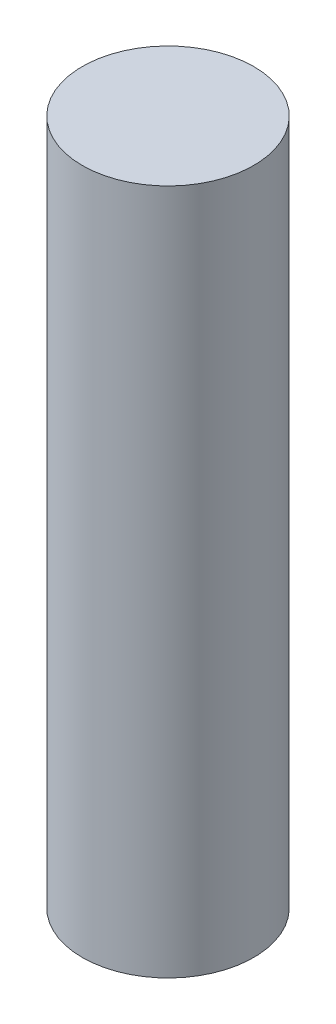
SolidWorks part; units mm, degrees
ref_plane "Alzado" through (0, 0, 0) normal (0, 0, 1) x (1, 0, 0)
ref_plane "Planta" through (0, 0, 0) normal (0, 1, 0) x (1, 0, 0)
ref_plane "Vista lateral" through (0, 0, 0) normal (1, 0, 0) x (0, 0, -1)
sketch "Croquis1" plane through (0, 0, 0) normal (0, 1, 0) x (1, 0, 0)
  circle A0 centre (0, 0) radius 3.75
  dimension "D1" = 7.5
extrude "Saliente-Extruir1" add sketch "Croquis1" along normal blind 30
